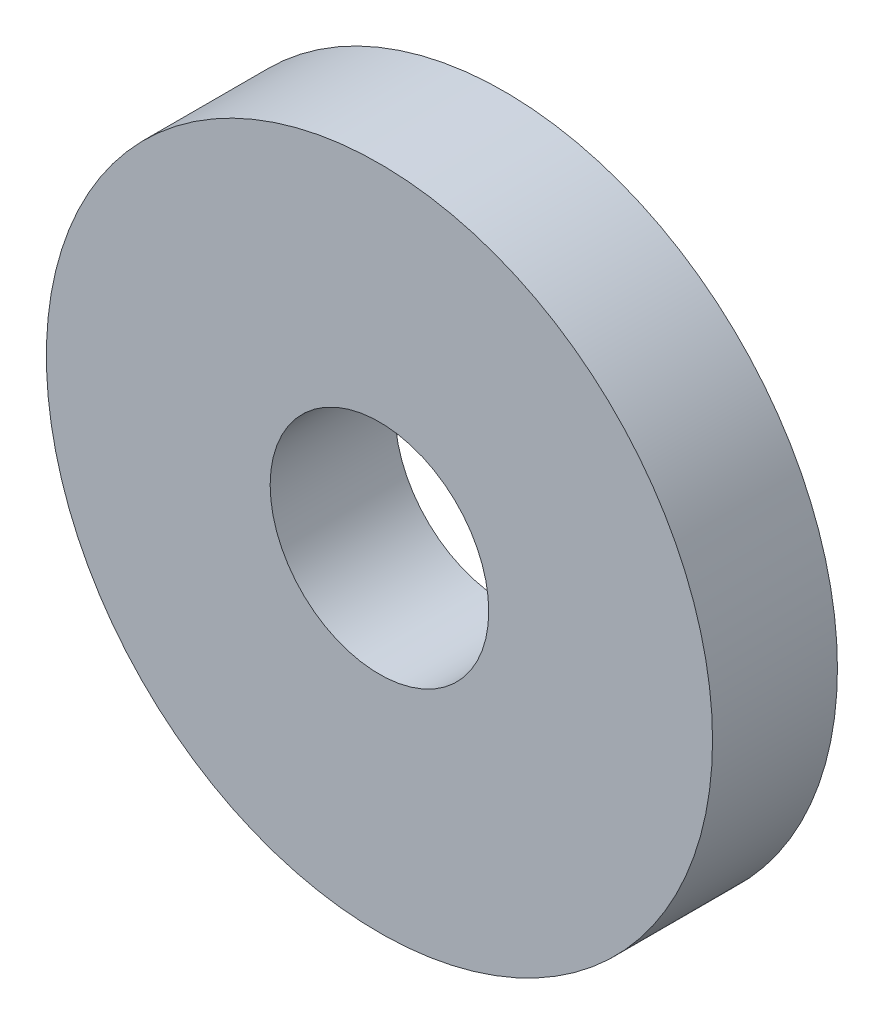
SolidWorks part; units mm, degrees
material "Alloy Steel (SS)"
ref_plane "Front Plane" through (0, 0, 0) normal (0, 0, 1) x (1, 0, 0)
ref_plane "Top Plane" through (0, 0, 0) normal (0, 1, 0) x (1, 0, 0)
ref_plane "Right Plane" through (0, 0, 0) normal (1, 0, 0) x (0, 0, -1)
sketch "Sketch1" plane through (0, 0, 0) normal (0, 0, 1) x (1, 0, 0)
  circle A0 centre (0, 0) radius 5.25
  circle A1 centre (0, 0) radius 16
  dimension "D1" = 32
  dimension "D2" = 10.5
extrude "Boss-Extrude1" add sketch "Sketch1" along normal blind 6
